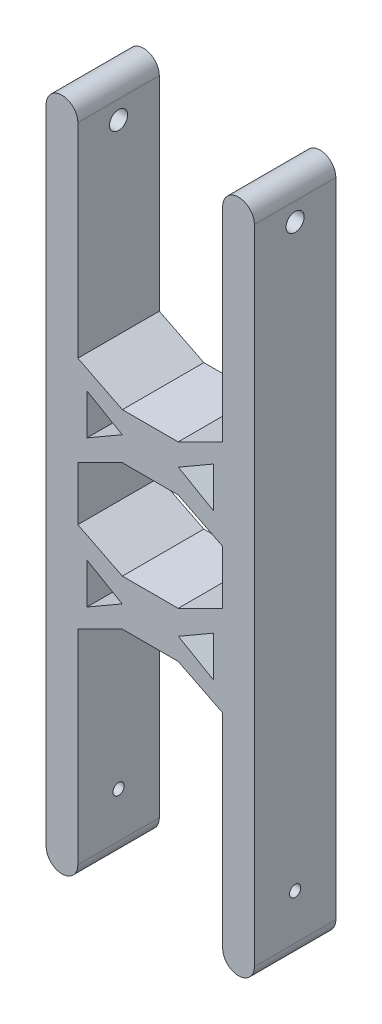
SolidWorks part; units mm, degrees
ref_plane "Front Plane" through (0, 0, 0) normal (0, 0, 1) x (1, 0, 0)
ref_plane "Top Plane" through (0, 0, 0) normal (0, 1, 0) x (1, 0, 0)
ref_plane "Right Plane" through (0, 0, 0) normal (1, 0, 0) x (0, 0, -1)
sketch "Sketch2" plane through (0, 0, 0) normal (0, 0, 1) x (1, 0, 0)
  line L0 (-20.32, 64.9071) -> (-20.32, 7.6604)
  line L1 (-29.21, 64.9071) -> (-29.21, -115.4329)
  line L2 (-17.78, -40.0991) -> (-17.78, -51.5291)
  line L3 (-17.78, -51.5291) -> (-7.8813, -45.8141)
  line L4 (-7.8813, -45.8141) -> (-17.78, -40.0991)
  line L5 (-20.32, -32.7862) -> (-7.8277, -39.0395)
  line L6 (-20.32, -58.1862) -> (-7.8277, -51.9329)
  line L7 (-29.21, -25.2629) -> (184.9737, -25.2629) construction
  line L8 (0, 129.1546) -> (0, -233.8246) construction
  line L9 (-17.78, 1.0033) -> (-7.8813, -4.7117)
  line L10 (-17.78, -10.4267) -> (-17.78, 1.0033)
  line L11 (-7.8813, -4.7117) -> (-17.78, -10.4267)
  line L12 (-20.32, 7.6604) -> (-7.8277, 1.4071)
  line L13 (-20.32, -17.7396) -> (-7.8277, -11.4863)
  line L14 (20.32, -58.1862) -> (7.8277, -51.9329)
  line L15 (17.78, -51.5291) -> (7.8813, -45.8141)
  line L16 (17.78, -40.0991) -> (17.78, -51.5291)
  line L17 (7.8813, -45.8141) -> (17.78, -40.0991)
  line L18 (20.32, -32.7862) -> (7.8277, -39.0395)
  line L19 (17.78, -10.4267) -> (17.78, 1.0033)
  line L20 (7.8813, -4.7117) -> (17.78, -10.4267)
  line L21 (17.78, 1.0033) -> (7.8813, -4.7117)
  line L22 (20.32, -17.7396) -> (7.8277, -11.4863)
  line L23 (20.32, 7.6604) -> (7.8277, 1.4071)
  line L24 (29.21, 64.9071) -> (29.21, -115.4329)
  line L25 (20.32, 64.9071) -> (20.32, 7.6604)
  line L26 (-7.8277, -39.0395) -> (7.8277, -39.0395)
  line L27 (-7.8277, -51.9329) -> (7.8277, -51.9329)
  line L28 (-7.8277, 1.4071) -> (7.8277, 1.4071)
  line L29 (-7.8277, -11.4863) -> (7.8277, -11.4863)
  line L30 (-20.32, -58.1862) -> (-20.32, -115.4329)
  line L31 (20.32, -58.1862) -> (20.32, -115.4329)
  line L32 (-20.32, -17.7396) -> (-20.32, -32.7862)
  line L33 (20.32, -17.7396) -> (20.32, -32.7862)
  arc A0 (-20.32, 64.9071) -> (-29.21, 64.9071) centre (-24.765, 64.9071) ccw
  arc A1 (-29.21, -115.4329) -> (-20.32, -115.4329) centre (-24.765, -115.4329) ccw
  arc A2 (20.32, 64.9071) -> (29.21, 64.9071) centre (24.765, 64.9071) cw
  arc A3 (29.21, -115.4329) -> (20.32, -115.4329) centre (24.765, -115.4329) cw
  point P44 (0, -39.0395)
  dimension "D3" = 11.43
  dimension "D1" = 180.34
  dimension "D2" = 8.89
  dimension "D4" = 2.54
  dimension "D5" = 25.4
  dimension "D6" = 13.97
  dimension "D7" = 12.4923
  dimension "D8" = 63.5
  dimension "D9" = 40.64
  dimension "D10" = 39.0395
  dimension "D11" = 6.7748
extrude "Boss-Extrude1" add sketch "Sketch2" along normal blind 22.86
sketch "Sketch3" plane through (-29.21, 0, 0) normal (-1, 0, 0) x (0, 0, 1)
  line L0 (11.43, 64.9071) -> (11.43, -115.4329) construction
  line L1 (22.86, 64.9071) -> (0, 64.9071) construction
  line L2 (22.86, -115.4329) -> (0, -115.4329) construction
  circle A0 centre (11.43, -102.7329) radius 1.5875
  dimension "D1" = 3.175
  dimension "D2" = 12.7
extrude "Cut-Extrude1" cut sketch "Sketch3" against normal through all
sketch "Sketch4" plane through (-29.21, 0, 0) normal (-1, 0, 0) x (0, 0, 1)
  line L0 (11.43, 64.9071) -> (11.43, -115.4329) construction
  line L1 (22.86, 64.9071) -> (0, 64.9071) construction
  line L2 (22.86, -115.4329) -> (0, -115.4329) construction
  circle A0 centre (11.43, 59.8271) radius 2.54
  dimension "D1" = 5.08
  dimension "D2" = 5.08
extrude "Cut-Extrude2" cut sketch "Sketch4" against normal through all
